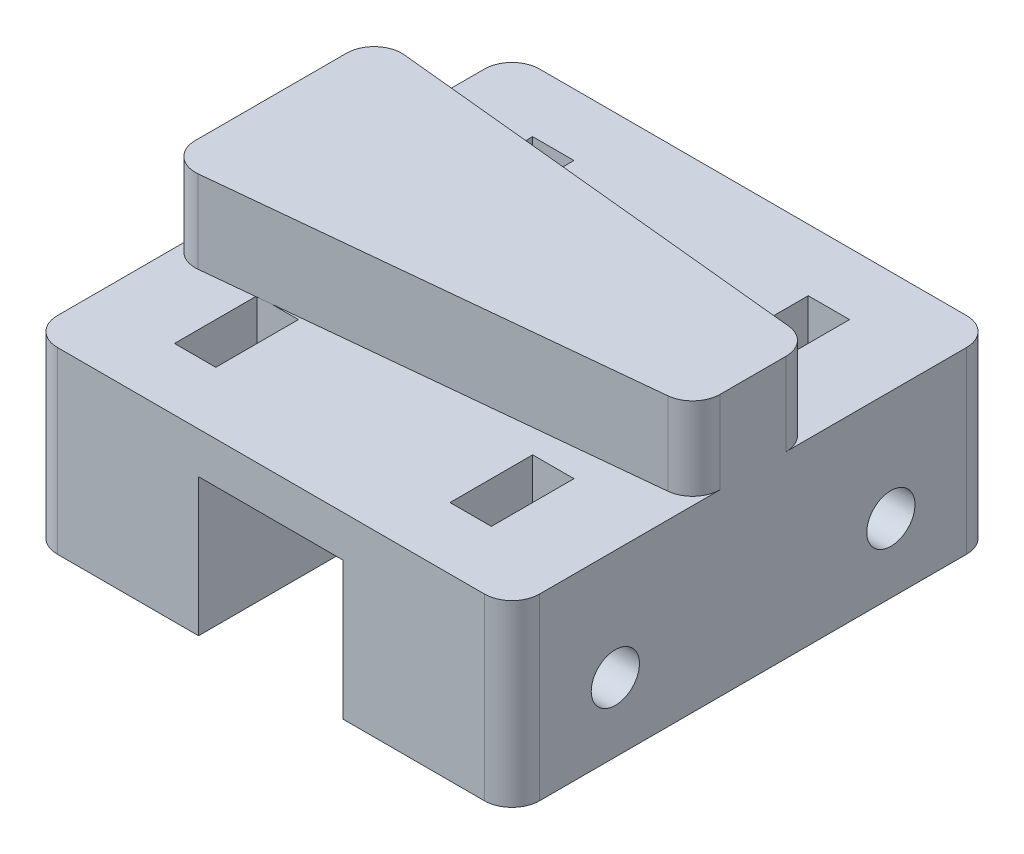
SolidWorks part; units mm, degrees
ref_plane "Спереди" through (0, 0, 0) normal (0, 0, 1) x (1, 0, 0)
ref_plane "Сверху" through (0, 0, 0) normal (0, 1, 0) x (1, 0, 0)
ref_plane "Справа" through (0, 0, 0) normal (1, 0, 0) x (0, 0, -1)
sketch "Эскиз1" plane through (0, 0, 0) normal (0, 1, 0) x (1, 0, 0)
  line L0 (-17.5, 7.5) -> (-17.5, -7.5)
  line L5 (-17.5, -7.5) -> (17.5, -4)
  line L6 (17.5, -4) -> (17.5, 4)
  line L7 (-17.5, 7.5) -> (17.5, 4)
  line L9 (-17.5, 0) -> (17.5, 0) construction
  line L10 (17.5, 0) -> (18.4404, 4.7489) construction
  line L12 (-5.25, 17.5) -> (5.25, 17.5) construction
  line L13 (-5.25, 17.5) -> (-5.25, -17.5)
  line L14 (-5.25, -17.5) -> (5.25, -17.5) construction
  line L15 (5.25, 17.5) -> (5.25, -17.5)
  line L16 (-5.25, 17.5) -> (5.25, -17.5) construction
  line L17 (-5.25, -17.5) -> (5.25, 17.5) construction
  line L21 (-17.5, -17.5) -> (17.5, -17.5)
  line L22 (-17.5, -17.5) -> (-17.5, 17.5)
  line L23 (-17.5, 17.5) -> (17.5, 17.5)
  line L24 (17.5, -17.5) -> (17.5, 17.5)
  line L25 (-17.5, -17.5) -> (17.5, 17.5) construction
  line L26 (-17.5, 17.5) -> (17.5, -17.5) construction
  point P0 (0, 0)
  point P4 (0, 0)
  dimension "D1" = 35
  dimension "D2" = 8
  dimension "D3" = 15
  dimension "D4" = 10.5
  dimension "D5" = 35
extrude "Бобышка-Вытянуть6" add sketch "Эскиз1" along normal blind 3 contours L21 L24 L23 L22
sketch "Эскиз5" plane through (0, 3, 0) normal (0, 1, 0) x (1, 0, 0)
  line L0 (-17.5, 7.5) -> (-17.5, -7.5)
  line L1 (-17.5, -7.5) -> (17.5, -4) construction
  line L2 (17.5, -4) -> (17.5, 4)
  line L3 (17.5, 4) -> (-17.5, 7.5) construction
  line L4 (-17.5, 7.5) -> (-17.5, 7.701)
  line L5 (-17.5, -17.5) -> (-17.5, 17.5) construction
  line L6 (-17.5, -7.5) -> (-17.5, -7.701)
  line L7 (-17.5, -7.701) -> (17.5, -4.201)
  line L8 (17.5, -17.5) -> (17.5, 17.5) construction
  line L9 (17.5, -4.201) -> (17.5, -4)
  line L10 (17.5, 4.201) -> (17.5, 4)
  line L11 (17.5, 4.201) -> (-17.5, 7.701)
  line L12 (17.5, -4) -> (17.5, -4.201)
  line M1 (-17.5, 17.5) -> (-17.5, -17.5)
  line M3 (17.5, -17.5) -> (17.5, 17.5)
  dimension "D1" = 0.2
  dimension "D2" = 0.2
extrude "Бобышка-Вытянуть7" add sketch "Эскиз5" along normal blind 6 contours L11 L7 M3 M1
sketch "Эскиз6" plane through (0, 0, 0) normal (0, -1, 0) x (1, 0, 0)
  line L1 (-17.5, -17.5) -> (-5.25, -17.5)
  line L2 (-17.5, -17.5) -> (-17.5, 17.5)
  line L3 (-17.5, 17.5) -> (-5.25, 17.5)
  line L4 (-5.25, -17.5) -> (-5.25, 17.5)
  line L5 (5.25, 17.5) -> (17.5, 17.5)
  line L6 (5.25, 17.5) -> (5.25, -17.5)
  line L7 (5.25, -17.5) -> (17.5, -17.5)
  line L8 (17.5, 17.5) -> (17.5, -17.5)
extrude "Бобышка-Вытянуть8" add sketch "Эскиз6" along normal blind 10
fillet "Скругление2" radius 2 8 edges at (17.5, -3.5, -17.5) (17.5, -3.5, 17.5) (-17.5, -3.5, -17.5) (-17.5, -3.5, 17.5) (17.5, 6, 4.201) (17.5, 6, -4.201) (-17.5, 6, -7.701) (-17.5, 6, 7.701)
sketch "Эскиз7" plane through (-17.5, 0, 0) normal (-1, 0, 0) x (0, 0, 1)
  line L0 (-15.5, -10) -> (-15.5, 0) construction
  line L1 (17.5, 0) -> (-17.5, 0) construction
  line L2 (-15.5, 3) -> (-15.5, -10) construction
  line L3 (-15.5, -5) -> (15.5, -5) construction
  line L4 (15.5, -10) -> (15.5, 3) construction
  circle A0 centre (-10, -5) radius 1.75
  circle A1 centre (0, -5) radius 1.75 construction
  circle A2 centre (10, -5) radius 1.75
  dimension "D1" = 3.5
  dimension "D2" = 3.5
  dimension "D3" = 3.5
  dimension "D4" = 10
  dimension "D5" = 10
sketch "Эскиз8" plane through (0, -10, 0) normal (0, -1, 0) x (1, 0, 0)
  line L0 (-17.5, 0) -> (17.5, 0) construction
  line L1 (17.5, -15.5) -> (17.5, 15.5) construction
  line L2 (-11.5, -7) -> (-8.5, -7)
  line L3 (-11.5, 3) -> (-8.5, 3) construction
  line L4 (-11.5, 3) -> (-11.5, -3) construction
  line L5 (-11.5, -3) -> (-8.5, -3) construction
  line L6 (-8.5, 3) -> (-8.5, -3) construction
  line L7 (-11.5, 3) -> (-8.5, -3) construction
  line L8 (-11.5, -3) -> (-8.5, 3) construction
  line L9 (8.5, 3) -> (11.5, 3) construction
  line L10 (8.5, 3) -> (8.5, -3) construction
  line L11 (8.5, -3) -> (11.5, -3) construction
  line L12 (11.5, 3) -> (11.5, -3) construction
  line L13 (8.5, 3) -> (11.5, -3) construction
  line L14 (8.5, -3) -> (11.5, 3) construction
  line L15 (-11.5, -7) -> (-11.5, -13)
  line L16 (-11.5, -13) -> (-8.5, -13)
  line L17 (-8.5, -7) -> (-8.5, -13)
  line L18 (8.5, -7) -> (11.5, -7)
  line L19 (8.5, -7) -> (8.5, -13)
  line L20 (8.5, -13) -> (11.5, -13)
  line L21 (11.5, -7) -> (11.5, -13)
  line L22 (-17.5, -10) -> (17.5, -10) construction
  line L23 (-11.5, -7) -> (-8.5, -13) construction
  line L24 (-11.5, -13) -> (-8.5, -7) construction
  line L25 (8.5, -7) -> (11.5, -13) construction
  line L26 (8.5, -13) -> (11.5, -7) construction
  line L27 (-11.5, 3) -> (-8.5, 3)
  line L28 (-11.5, 3) -> (-11.5, -3)
  line L29 (-11.5, -3) -> (-8.5, -3)
  line L30 (-8.5, 3) -> (-8.5, -3)
  line L31 (8.5, 3) -> (11.5, 3)
  line L32 (8.5, 3) -> (8.5, -3)
  line L33 (8.5, -3) -> (11.5, -3)
  line L34 (11.5, 3) -> (11.5, -3)
  line L35 (-17.5, 0) -> (17.5, 0) construction
  line L36 (-11.5, 3) -> (-8.5, -3) construction
  line L37 (-11.5, -3) -> (-8.5, 3) construction
  line L38 (8.5, 3) -> (11.5, -3) construction
  line L39 (8.5, -3) -> (11.5, 3) construction
  line L40 (-11.5, 13) -> (-8.5, 13)
  line L41 (-11.5, 13) -> (-11.5, 7)
  line L42 (-11.5, 7) -> (-8.5, 7)
  line L43 (-8.5, 13) -> (-8.5, 7)
  line L44 (8.5, 13) -> (11.5, 13)
  line L45 (8.5, 13) -> (8.5, 7)
  line L46 (8.5, 7) -> (11.5, 7)
  line L47 (11.5, 13) -> (11.5, 7)
  line L48 (-17.5, 10) -> (17.5, 10) construction
  line L49 (-11.5, 13) -> (-8.5, 7) construction
  line L50 (-11.5, 7) -> (-8.5, 13) construction
  line L51 (8.5, 13) -> (11.5, 7) construction
  line L52 (8.5, 7) -> (11.5, 13) construction
  point P0 (-10, 0)
  point P6 (0, 0)
  point P12 (10, 0)
  point P18 (-10, -10)
  point P22 (0, -10)
  point P27 (10, -10)
  point P32 (-10, 0)
  point P35 (0, 0)
  point P40 (10, 0)
  point P45 (-10, 10)
  point P48 (0, 10)
  point P53 (10, 10)
  dimension "D1" = 3
  dimension "D2" = 3
  dimension "D3" = 6
  dimension "D4" = 6
  dimension "D5" = 10
  dimension "D6" = 10
  dimension "D7" = 2
  dimension "D8" = 2
extrude "Вырез-Вытянуть3" cut sketch "Эскиз7" against normal through all
extrude "Вырез-Вытянуть4" cut sketch "Эскиз8" against normal up to surface (13 mm away) contours L21 L18 L19 L20 | L17 L16 L15 L2 | L43 L42 L41 L40 | L47 L46 L45 L44 | L10 L9 L12 L11
sketch "Эскиз11" plane through (0, 6.5, 0) normal (0, 1, 0) x (1, 0, 0)
  line L0 (-10, 0) -> (10, 0) construction
  line L1 (-8.2679, -3) -> (-6.5359, 0)
  line L2 (-6.5359, 0) -> (-8.2679, 3)
  line L3 (-8.2679, 3) -> (-11.7321, 3)
  line L4 (-11.7321, 3) -> (-13.4641, 0)
  line L5 (-13.4641, 0) -> (-11.7321, -3)
  line L6 (-11.7321, -3) -> (-8.2679, -3)
  line L7 (6.5359, 0) -> (8.2679, -3)
  line L8 (8.2679, -3) -> (11.7321, -3)
  line L9 (11.7321, -3) -> (13.4641, 0)
  line L10 (13.4641, 0) -> (11.7321, 3)
  line L11 (11.7321, 3) -> (8.2679, 3)
  line L12 (8.2679, 3) -> (6.5359, 0)
  line L15 (-10, 13) -> (-10, -13) construction
  line L16 (-8.5, 13) -> (-11.5, 13) construction
  line L17 (-8.5, -13) -> (-11.5, -13) construction
  circle A0 centre (-10, 0) radius 3 construction
  circle A1 centre (10, 0) radius 3 construction
  point P26 (0, 0)
  dimension "D1" = 6
  dimension "D2" = 6
extrude "Вырез-Вытянуть5" cut sketch "Эскиз11" against normal blind 4
sketch "Эскиз12" plane through (0, 2.5, 0) normal (0, 1, 0) x (1, 0, 0)
  line L0 (-11.7321, 3) -> (-8.2679, -3) construction
  line L1 (-8.2679, -3) -> (-11.7321, -3) construction
  line L2 (-11.7321, -3) -> (-8.2679, 3) construction
  line L3 (-8.2679, 3) -> (-11.7321, 3) construction
  line L4 (7, 1.7321) -> (13, -1.7321) construction
  line L5 (13, -1.7321) -> (13, 1.7321) construction
  line L6 (13, -1.7321) -> (13, 1.7321) construction
  line L7 (13, 1.7321) -> (7, -1.7321) construction
  line L8 (7, -1.7321) -> (7, 1.7321) construction
  circle A0 centre (-10, 0) radius 1.75
  circle A1 centre (10, 0) radius 1.75
  dimension "D1" = 3.5
  dimension "D2" = 3.5
extrude "Вырез-Вытянуть6" cut sketch "Эскиз12" against normal through all
sketch "Эскиз13" plane through (0, -10, 0) normal (0, -1, 0) x (1, 0, 0)
  line L0 (5.25, -17.5) -> (-5.25, -17.5)
  line L1 (-5.25, 17.5) -> (5.25, 17.5)
  line L2 (11.5, -7) -> (11.5, -13) construction
  line L3 (8.5, -13) -> (11.5, -13) construction
  line L4 (-17.5, 15.5) -> (-17.5, -15.5)
  line L5 (-15.5, -17.5) -> (-5.25, -17.5)
  line L6 (-5.25, -17.5) -> (-5.25, 17.5)
  line L7 (-5.25, 17.5) -> (-15.5, 17.5)
  line L8 (-17.5, 15.5) -> (-17.5, -15.5)
  line L9 (-15.5, -17.5) -> (-5.25, -17.5)
  line L10 (-5.25, -17.5) -> (-5.25, 17.5)
  line L11 (-5.25, 17.5) -> (-15.5, 17.5)
  line L12 (5.25, -17.5) -> (15.5, -17.5)
  line L13 (17.5, -15.5) -> (17.5, 15.5)
  line L14 (15.5, 17.5) -> (5.25, 17.5)
  line L15 (5.25, 17.5) -> (5.25, -17.5)
  line L16 (5.25, -17.5) -> (15.5, -17.5)
  line L17 (17.5, -15.5) -> (17.5, 15.5)
  line L18 (15.5, 17.5) -> (5.25, 17.5)
  line L19 (5.25, 17.5) -> (5.25, -17.5)
  line L20 (8.5, -7) -> (8.5, -13) construction
  line L21 (8.5, -7) -> (11.5, -7) construction
  line L22 (8.5, 7) -> (11.5, 7) construction
  line L23 (11.5, 13) -> (11.5, 7) construction
  line L24 (8.5, 13) -> (11.5, 13) construction
  line L25 (8.5, 13) -> (8.5, 7) construction
  line L26 (-11.5, 7) -> (-8.5, 7) construction
  line L27 (-8.5, 13) -> (-8.5, 7) construction
  line L28 (-11.5, 13) -> (-8.5, 13) construction
  line L29 (-11.5, 13) -> (-11.5, 7) construction
  line L30 (-11.5, -13) -> (-8.5, -13) construction
  line L31 (-8.5, -7) -> (-8.5, -13) construction
  line L32 (-11.5, -7) -> (-8.5, -7) construction
  line L33 (-11.5, -7) -> (-11.5, -13) construction
  line L34 (11.5, -7) -> (11.5, -13)
  line L35 (8.5, -13) -> (11.5, -13)
  line L36 (8.5, -7) -> (8.5, -13)
  line L37 (8.5, -7) -> (11.5, -7)
  line L38 (8.5, 7) -> (11.5, 7)
  line L39 (11.5, 13) -> (11.5, 7)
  line L40 (8.5, 13) -> (11.5, 13)
  line L41 (8.5, 13) -> (8.5, 7)
  line L42 (-11.5, 7) -> (-8.5, 7)
  line L43 (-8.5, 13) -> (-8.5, 7)
  line L44 (-11.5, 13) -> (-8.5, 13)
  line L45 (-11.5, 13) -> (-11.5, 7)
  line L46 (-11.5, -13) -> (-8.5, -13)
  line L47 (-8.5, -7) -> (-8.5, -13)
  line L48 (-11.5, -7) -> (-8.5, -7)
  line L49 (-11.5, -7) -> (-11.5, -13)
  circle A0 centre (10, 0) radius 1.75 construction
  circle A1 centre (-10, 0) radius 1.75 construction
  arc A2 (-17.5, -15.5) -> (-15.5, -17.5) centre (-15.5, -15.5) ccw
  arc A3 (-15.5, 17.5) -> (-17.5, 15.5) centre (-15.5, 15.5) ccw
  arc A4 (-17.5, -15.5) -> (-15.5, -17.5) centre (-15.5, -15.5) ccw
  arc A5 (-15.5, 17.5) -> (-17.5, 15.5) centre (-15.5, 15.5) ccw
  arc A6 (15.5, -17.5) -> (17.5, -15.5) centre (15.5, -15.5) ccw
  arc A7 (17.5, 15.5) -> (15.5, 17.5) centre (15.5, 15.5) ccw
  arc A8 (15.5, -17.5) -> (17.5, -15.5) centre (15.5, -15.5) ccw
  arc A9 (17.5, 15.5) -> (15.5, 17.5) centre (15.5, 15.5) ccw
  circle A10 centre (10, 0) radius 1.75
  circle A11 centre (-10, 0) radius 1.75
  dimension "D1" = 0
  dimension "D2" = 0
ref_plane "Плоскость1" through (0, 0, 0) normal (0, 0, 1) x (1, 0, 0)
